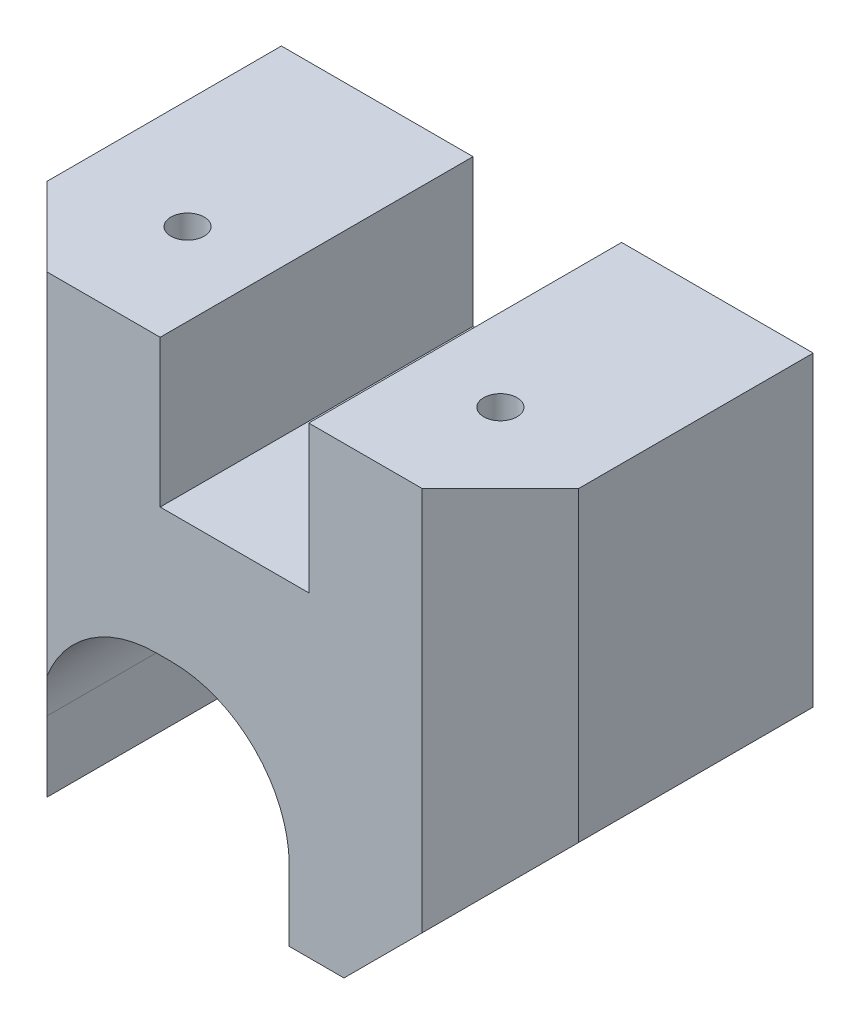
SolidWorks part; units mm, degrees
material "Nylon 6/10"
ref_plane "Front Plane" through (0, 0, 0) normal (0, 0, 1) x (1, 0, 0)
ref_plane "Top Plane" through (0, 0, 0) normal (0, 1, 0) x (1, 0, 0)
ref_plane "Right Plane" through (0, 0, 0) normal (1, 0, 0) x (0, 0, -1)
sketch "Sketch1" plane through (0, 0, 0) normal (0, 1, 0) x (1, 0, 0)
  line L1 (-21.59, -12.7) -> (21.59, -12.7)
  line L2 (-21.59, -12.7) -> (-21.59, 12.7)
  line L3 (-21.59, 12.7) -> (21.59, 12.7)
  line L4 (21.59, -12.7) -> (21.59, 12.7)
  line L5 (-21.59, -12.7) -> (21.59, 12.7) construction
  line L6 (-21.59, 12.7) -> (21.59, -12.7) construction
  point P0 (0, 0)
  dimension "D1" = 25.4
  dimension "D2" = 43.18
extrude "Base" add sketch "Sketch1" along normal blind 37.592
chamfer "SideChamfer" distance 12.7 angle 45 1 edges at (21.59, 0, 0)
chamfer "BackChamfers" distance 6.35 angle 45 2 edges at (-21.59, 18.796, 12.7) (21.59, 25.146, 12.7)
sketch "Sketch2" plane through (0, 0, 12.7) normal (0, 0, 1) x (1, 0, 0)
  line L1 (-6.0325, 37.592) -> (6.0325, 37.592)
  line L2 (-6.0325, 37.592) -> (-6.0325, 25.654)
  line L3 (-6.0325, 25.654) -> (6.0325, 25.654)
  line L4 (6.0325, 37.592) -> (6.0325, 25.654)
  line L5 (-6.0325, 37.592) -> (6.0325, 25.654) construction
  line L6 (-6.0325, 25.654) -> (6.0325, 37.592) construction
  line L7 (0, 25.654) -> (0, 37.592) construction
  line L8 (-15.24, 37.592) -> (15.24, 37.592) construction
  point P0 (0, 31.623)
  dimension "D1" = 11.938
  dimension "D2" = 12.065
extrude "LinActSlot" cut sketch "Sketch2" against normal through all
hole_wizard "MoutingHoles" positions "Sketch4" profile "Sketch3" tap size "#6-32" standard "ANSI Inch"
sketch "Sketch4" plane through (14.1604, 37.592, 8.3734) normal (0, -1, 0) x (-1, 0, 0)
  line L0 (14.1604, 8.3734) -> (14.1604, 11.4563) construction
  line L3 (29.4004, -4.3266) -> (20.1929, -4.3266) construction
  point P0 (1.4604, 4.5634)
  point P2 (26.8604, 4.5634)
  dimension "D1" = 25.4
  dimension "D2" = 8.89
sketch "Sketch3" plane through (12.7, 37.592, 3.81) normal (1, 0, 0) x (0, 0, 1)
  line L0 (0, 0) -> (0, 15.2907)
  line L1 (0, 15.2907) -> (1.3525, 14.478)
  line L2 (1.3525, 14.478) -> (1.3525, 0)
  line L5 (1.3525, 0) -> (0, 0)
  line L10 (0, 15.2907) -> (-1.3526, 14.478) construction
  line L11 (0, -6.35) -> (0, 107.95) construction
  dimension "Tap Drill Dia." = 2.7051
  dimension "Tap Drill Depth" = 14.478
  dimension "Drill Angle" = 118
sketch "Sketch11" plane through (0, 0, -12.7) normal (0, 0, -1) x (-1, 0, 0)
  line L0 (-8.89, 0) -> (21.59, 0) construction
  line L1 (15.875, 5.08) -> (15.875, 5.715)
  line L2 (6.35, 15.24) -> (5.08, 15.24)
  line L3 (21.59, 37.592) -> (21.59, 0) construction
  line L4 (15.875, 5.08) -> (15.875, 0)
  line L5 (-8.89, 0) -> (21.59, 0) construction
  line L6 (15.875, 0) -> (-4.445, 0)
  line L7 (-4.445, 0) -> (-4.445, 5.08)
  line L8 (-4.445, 5.715) -> (-4.445, 5.08)
  arc A0 (15.875, 5.08) -> (-4.445, 5.08) centre (5.715, 5.08) ccw construction
  arc A1 (-4.445, 5.715) -> (5.08, 15.24) centre (5.08, 5.715) cw
  arc A2 (6.35, 15.24) -> (15.875, 5.715) centre (6.35, 5.715) cw
  dimension "D1" = 20.32
  dimension "D4" = 9.525
  dimension "D2" = 5.08
  dimension "D3" = 15.875
extrude "MotorSlot" cut sketch "Sketch11" against normal through all
hole_wizard "MotorMountingHoles2" positions "Sketch13" profile "Sketch12" tap size "#4-40" standard "ANSI Inch"
sketch "Sketch13" plane through (0, 0, -12.7) normal (0, 0, -1) x (-1, 0, 0)
  line L7 (6.35, 15.24) -> (5.08, 15.24) construction
  line L8 (6.35, 15.24) -> (5.08, 15.24) construction
  line L9 (5.715, 15.24) -> (5.715, -3.6836) construction
  arc A2 (15.875, 5.715) -> (6.35, 15.24) centre (6.35, 5.715) ccw construction
  arc A3 (15.875, 5.715) -> (6.35, 15.24) centre (6.35, 5.715) ccw construction
  point P0 (18.215, 5.715)
  point P2 (-6.785, 5.715)
  dimension "D1" = 25
sketch "Sketch12" plane through (-18.215, 5.715, -12.7) normal (1, 0, 0) x (0, 1, 0)
  line L0 (0, 0) -> (0, 12.1092)
  line L1 (0, 12.1092) -> (1.1303, 11.43)
  line L2 (1.1303, 11.43) -> (1.1303, 0)
  line L5 (1.1303, 0) -> (0, 0)
  line L10 (0, 12.1092) -> (-1.1303, 11.43) construction
  line L11 (0, -6.35) -> (0, 107.95) construction
  dimension "Tap Drill Dia." = 2.2606
  dimension "Tap Drill Depth" = 11.43
  dimension "Drill Angle" = 118
cosmetic thread "Hole Thread4" parameters "D1"=9.398, "D2"=2.8448
cosmetic thread "Hole Thread5" parameters "D1"=9.398, "D2"=2.8448
hole_wizard "GripperSetScrew" [suppressed] positions "Sketch15" profile "Sketch14" tap size "#4-40" standard "ANSI Inch"
sketch "Sketch15" plane through (0, 18.542, 0) normal (0, 1, 0) x (1, 0, 0)
  line L0 (0, 0) -> (0, -19.304) construction
  line L1 (-6.0325, -19.304) -> (6.0325, -19.304) construction
  point P0 (0, -12.954)
  dimension "D1" = 6.35
sketch "Sketch14" plane through (0, 18.542, 12.954) normal (1, 0, 0) x (0, 0, 1)
  line L0 (0, 0) -> (0, 18.542)
  line L1 (0, 18.542) -> (1.1303, 18.542)
  line L2 (1.1303, 18.542) -> (1.1303, 0)
  line L5 (1.1303, 0) -> (0, 0)
  line L11 (0, -6.35) -> (0, 107.95) construction
  dimension "Thru Tap Drill Dia." = 2.2606
  dimension "Thru Tap Drill Depth" = 18.542
cosmetic thread "Hole Thread6" [suppressed] parameters "D2"=2.8448
